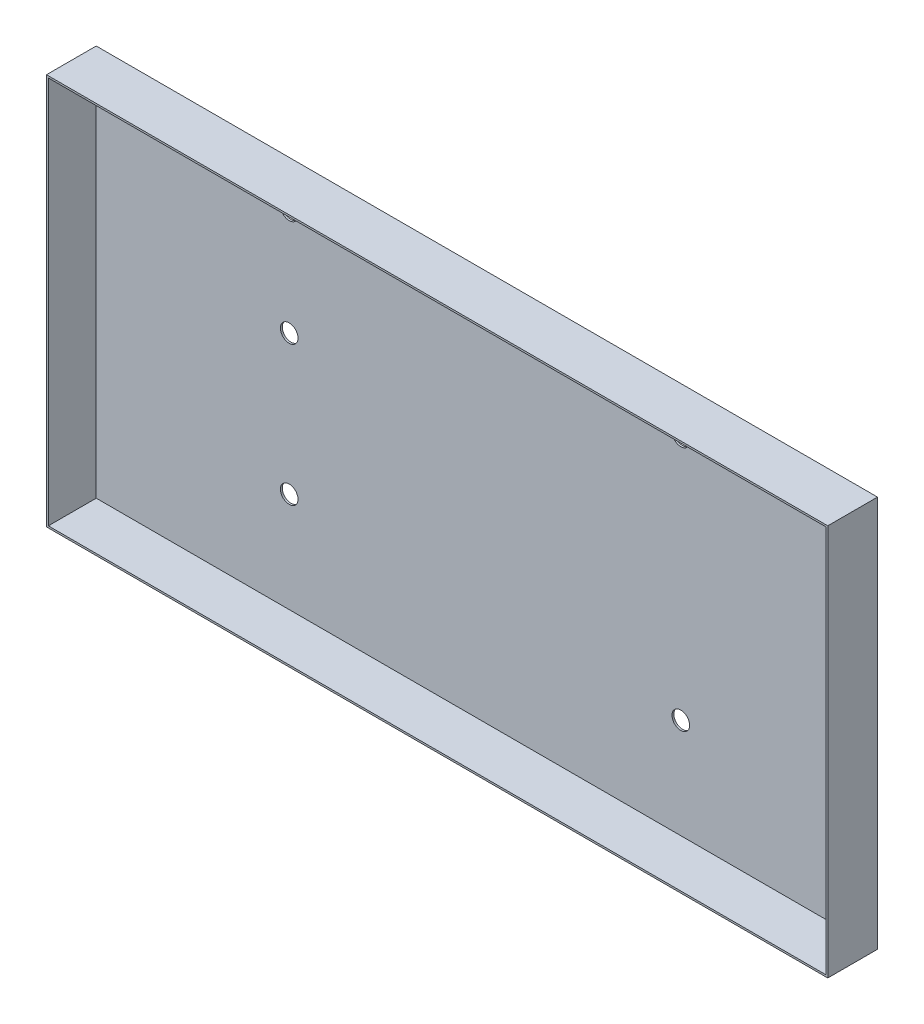
SolidWorks part; units mm, degrees
ref_plane "Alzado" through (0, 0, 0) normal (0, 0, 1) x (1, 0, 0)
ref_plane "Planta" through (0, 0, 0) normal (0, 1, 0) x (1, 0, 0)
ref_plane "Vista lateral" through (0, 0, 0) normal (1, 0, 0) x (0, 0, -1)
sketch "Croquis1" plane through (0, 0, 0) normal (0, 0, 1) x (1, 0, 0)
  line L0 (-798, 400) -> (-798, 0)
  line L1 (-798, 0) -> (0, 0)
  line L2 (0, 0) -> (0, 400)
  line L3 (0, 400) -> (-798, 400)
  circle A0 centre (-599, 355) radius 9
  circle A1 centre (-599, 246.5) radius 9
  circle A2 centre (-599, 104) radius 9
  circle A3 centre (-199, 104) radius 9
  circle A4 centre (-199, 355) radius 9
  dimension "D3" = 18
  dimension "D5" = 18
  dimension "D6" = 18
  dimension "D7" = 18
  dimension "D8" = 18
  dimension "D10" = 108.5
  dimension "D11" = 142.5
  dimension "D12" = 251
  dimension "D15" = 199
  dimension "D16" = 199
  dimension "D1" = 400
  dimension "D2" = 798
  dimension "D4" = 45
  dimension "D9" = 45
  dimension "D13" = 199
  dimension "D14" = 199
  dimension "D17" = 199
extrude "Saliente-Extruir1" add sketch "Croquis1" along normal blind 50.8
shell "Vaciado1" thickness 1.9
sketch "Croquis2" plane through (0, 0, 50.8) normal (0, 0, 1) x (1, 0, 0)
  line L0 (-1.9, 1.9) -> (-1.9, 398.1)
  line L1 (-1.9, 398.1) -> (-796.1, 398.1)
  line L2 (-796.1, 398.1) -> (-796.1, 1.9)
  line L3 (-796.1, 1.9) -> (-1.9, 1.9)
extrude "Cortar-Extruir1" cut sketch "Croquis2" against normal blind 48.9
